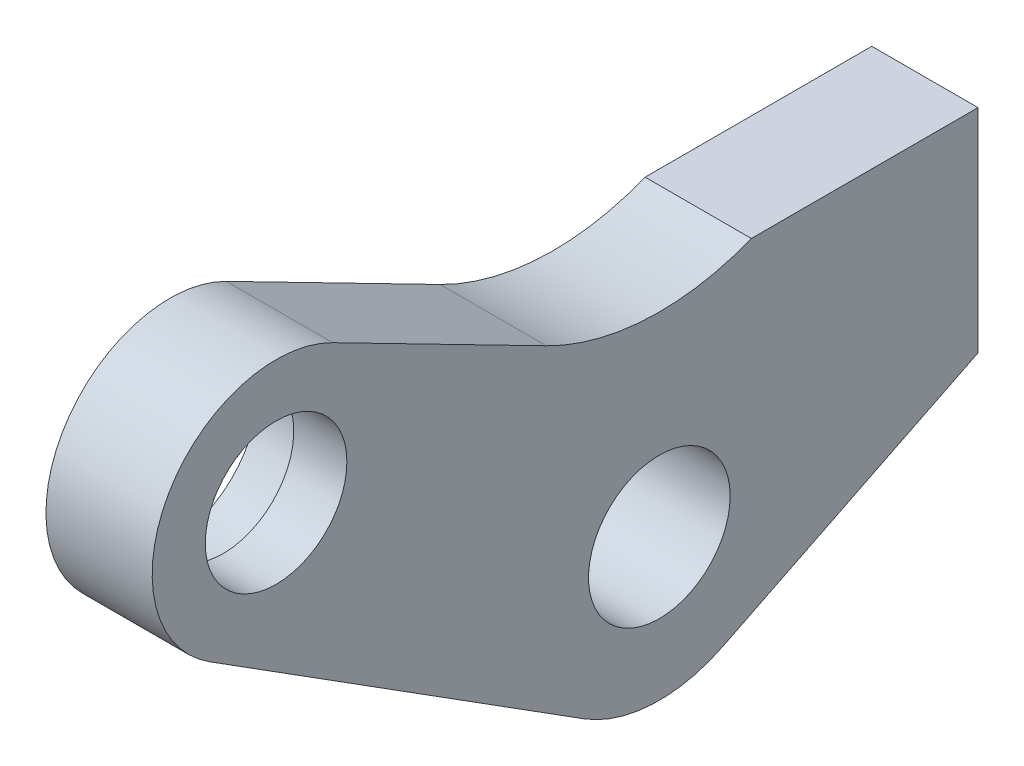
SolidWorks part; units mm, degrees
ref_plane "Front Plane" through (0, 0, 0) normal (0, 0, 1) x (1, 0, 0)
ref_plane "Top Plane" through (0, 0, 0) normal (0, 1, 0) x (1, 0, 0)
ref_plane "Right Plane" through (0, 0, 0) normal (1, 0, 0) x (0, 0, -1)
sketch "Sketch2" plane through (0, 0, 0) normal (1, 0, 0) x (0, 0, -1)
  line L0 (-47.8068, 48.2293) -> (-35.7357, 42.0415)
  line L1 (-54.7397, 36.0827) -> (-33.6233, 22.7373)
  line L2 (-11.3494, 41.5) -> (-11.3494, 29.5)
  line L3 (-20.8494, 54.5) -> (-37.8494, 54.5) construction
  line L4 (-11.3494, 29.5) -> (-25.7938, 22.3335)
  line L5 (-60, 0) -> (0, 0) construction
  line L6 (-60, 0) -> (-60, 58) construction
  line L7 (-60, 58) -> (0, 58) construction
  line L8 (0, 0) -> (0, 58) construction
  line L9 (-11.3494, 29.5) -> (-17.3494, 29.5) construction
  line L10 (-11.3494, 29.5) -> (-11.3494, 41.5) construction
  line L11 (-11.3494, 41.5) -> (-17.3494, 41.5) construction
  line L12 (-17.3494, 29.5) -> (-17.3494, 41.5) construction
  line L13 (-11.3494, 41.5) -> (-24.1532, 41.5)
  arc A0 (-54.7397, 36.0827) -> (-47.8068, 48.2293) centre (-51, 42) cw
  circle A1 centre (-29.3494, 54.5) radius 12.5 construction
  arc A2 (-35.7357, 42.0415) -> (-24.1532, 41.5) centre (-29.3494, 54.5) ccw
  circle A3 centre (-29.3494, 54.5) radius 3.55 construction
  circle A4 centre (-29.3494, 29.5) radius 8.5 construction
  circle A5 centre (-51, 42) radius 4
  arc A6 (-33.6233, 22.7373) -> (-25.7938, 22.3335) centre (-29.3494, 29.5) ccw
  circle A7 centre (-20.8494, 54.5) radius 1.5 construction
  circle A8 centre (-37.8494, 54.5) radius 1.5 construction
  circle A9 centre (-20.8494, 54.5) radius 3.25 construction
  circle A10 centre (-37.8494, 54.5) radius 3.25 construction
  circle A11 centre (-29.3494, 29.5) radius 4
  dimension "D5" = 8
  dimension "D6" = 25
  dimension "D8" = 7.1
  dimension "D10" = 3
  dimension "D12" = 6.5
  dimension "D15" = 8
  dimension "D16" = 7
  dimension "D17" = 8
  dimension "D18" = 17
  dimension "D23" = 14
  dimension "D1" = 60
  dimension "D2" = 58
  dimension "D3" = 42
  dimension "D4" = 9
  dimension "D7" = 18
  dimension "D9" = 25
  dimension "D11" = 8.5
  dimension "D13" = 25
  dimension "D14" = 25
  dimension "D19" = 6
  dimension "D20" = 12
extrude "Boss-Extrude1" add sketch "Sketch2" along normal blind 6
sketch "Sketch3" plane through (0, 0, 0) normal (-1, 0, 0) x (0, 0, 1)
  circle A0 centre (51, 42) radius 4.99
  dimension "D1" = 9.98
extrude "Cut-Extrude1" cut sketch "Sketch3" against normal blind 3
